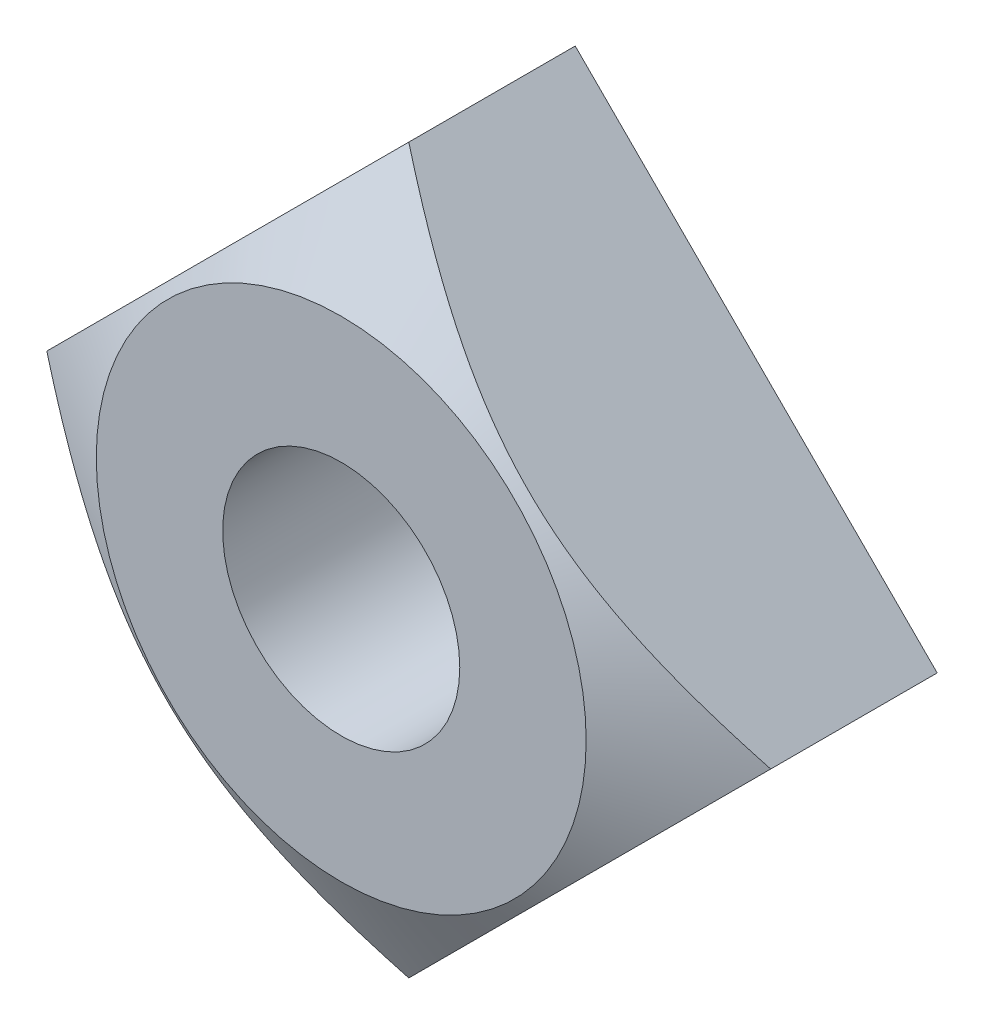
SolidWorks part; units mm, degrees
ref_plane "前视基准面" through (0, 0, 0) normal (0, 0, 1) x (1, 0, 0)
ref_plane "上视基准面" through (0, 0, 0) normal (0, 1, 0) x (1, 0, 0)
ref_plane "右视基准面" through (0, 0, 0) normal (1, 0, 0) x (0, 0, -1)
sketch "草图4" plane through (0, 0, 0) normal (0, 0, 1) x (1, 0, 0)
  line L0 (-4.9497, 0) -> (4.9497, 0) construction
  line L1 (0, 4.9497) -> (0, -4.9497) construction
  line L6 (4.9497, 0) -> (0, 4.9497)
  line L7 (-4.9497, 0) -> (0, 4.9497)
  line L10 (4.9497, 0) -> (0, -4.9497)
  line L11 (-4.9497, 0) -> (0, -4.9497)
  circle A0 centre (0, 0) radius 2 construction
  circle A1 centre (0, 0) radius 1.6211
  dimension "D1" = 90
  dimension "D" = 4
  dimension "D3" = 3.2422
  dimension "s(max)" = 7
sketch "草图5" plane through (0, 0, 0) normal (1, 0, 0) x (0, 0, -1)
  line L0 (0.9238, -4.9497) -> (0, -3.3497)
  line L1 (0, 3.3497) -> (0, -3.3497)
  line L2 (0.9238, 4.9497) -> (3.2, 4.9497)
  line L3 (3.2, 4.9497) -> (3.2, -4.9497)
  line L4 (0.9238, -4.9497) -> (3.2, -4.9497)
  line L5 (0, 2) -> (3.2, 2)
  line L6 (0, 1.6211) -> (3.2, 1.6211)
  line L7 (0.9238, 4.9497) -> (0, 3.3497)
  line L8 (0, 0) -> (3.2, 0) construction
  line L9 (0, 0) -> (0, 4.9497) construction
  line L10 (0, 2) -> (-0.2187, 1.6211)
  line L11 (0, 2) -> (0.2187, 1.6211)
  line L12 (0.2187, 1.6211) -> (-0.2187, 1.6211)
  line L13 (0, 0) -> (0, 4.9497)
  line L16 (-0.139, -4.9497) -> (-0.139, 3.6803) construction
  point P12 (1.6238, 4.9497)
  dimension "D1" = 3.339
  dimension "m(min)" = 3.2
  dimension "D2" = 30
  dimension "D3" = 4
  dimension "D4" = 3.2422
  dimension "D5" = 60
  dimension "D6" = 60
  dimension "D7" = 1.6
  dimension "e(min)" = 8.63
  dimension "P" = 0.7
sketch "草图7" plane through (0, 0, 0) normal (0, 0, 1) x (1, 0, 0)
  line L4 (-4.9497, 0) -> (0, 4.9497) construction
  line L7 (4.9497, 0) -> (0, 4.9497) construction
  line L8 (-4.9497, 0) -> (0, 4.9497)
  line L9 (-4.9497, 0) -> (0, -4.9497) construction
  line L10 (4.9497, 0) -> (0, -4.9497) construction
  line L11 (4.9497, 0) -> (0, 4.9497)
  line L12 (-4.9497, 0) -> (0, -4.9497)
  line L13 (4.9497, 0) -> (0, -4.9497)
  circle A1 centre (0, 0) radius 1.6211 construction
  circle A2 centre (0, 0) radius 1.6211
extrude "凸台-拉伸1" add sketch "草图7" against normal up to vertex (3.2 mm away) up to point (0, 4.9497, -3.2)
cosmetic thread "装饰螺纹线1" parameters "D2"=4
sketch "草图8" plane through (0, 0, 0) normal (1, 0, 0) x (0, 0, -1)
  line L9 (0.9238, 4.9497) -> (0, 3.3497) construction
  line L10 (0, 4.9497) -> (0, -4.9497) construction
  line L11 (3.2, 4.9497) -> (0, 4.9497) construction
  line L13 (0.9238, 4.9497) -> (0, 3.3497)
  line L14 (0, 4.9497) -> (0, 3.3497)
  line L15 (0.9238, 4.9497) -> (0, 4.9497)
  line L16 (0, 0) -> (3.2, 0) construction
revolve "切除-旋转1" cut sketch "草图8" angle 360 about L16
